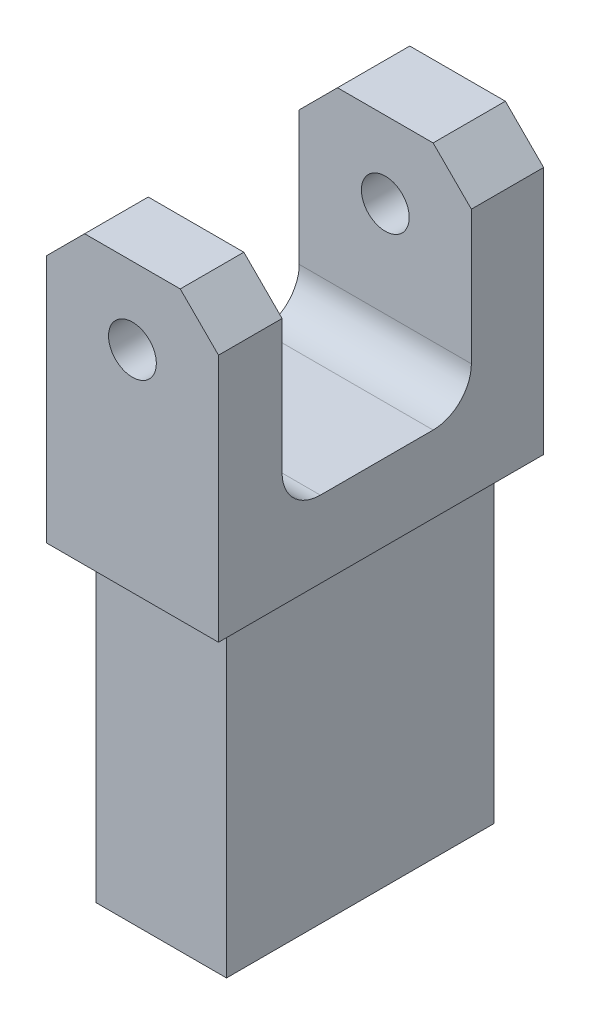
SolidWorks part; units mm, degrees
ref_plane "Спереди" through (0, 0, 0) normal (0, 0, 1) x (1, 0, 0)
ref_plane "Сверху" through (0, 0, 0) normal (0, 1, 0) x (1, 0, 0)
ref_plane "Справа" through (0, 0, 0) normal (1, 0, 0) x (0, 0, -1)
sketch "Эскиз1" plane through (0, 0, 0) normal (0, 1, 0) x (1, 0, 0)
  line L1 (1.598, -22.6241) -> (15.2463, -22.6241)
  line L2 (1.598, -22.6241) -> (1.598, -50.5962)
  line L3 (1.598, -50.5962) -> (15.2463, -50.5962)
  line L4 (15.2463, -22.6241) -> (15.2463, -50.5962)
extrude "Вытянуть1" add sketch "Эскиз1" along normal blind 33 from offset 18 offset against normal yes
sketch "Эскиз3" plane through (0, 15, 0) normal (0, 1, 0) x (1, 0, 0)
  line L0 (1.598, -36.6102) -> (-17.2651, -36.6102) construction
  line L2 (8.4222, -22.6241) -> (8.4222, -57.0135) construction
  line L4 (1.598, -50.5962) -> (15.2463, -50.5962) construction
  line L5 (15.2463, -50.5962) -> (15.2463, -22.6241) construction
  line L7 (17.4222, -53.6102) -> (-0.5778, -53.6102)
  line L8 (17.4222, -53.6102) -> (17.4222, -19.6102)
  line L9 (17.4222, -19.6102) -> (-0.5778, -19.6102)
  line L10 (-0.5778, -53.6102) -> (-0.5778, -19.6102)
  line L11 (17.4222, -53.6102) -> (-0.5778, -19.6102) construction
  line L12 (17.4222, -19.6102) -> (-0.5778, -53.6102) construction
  point P7 (8.4222, -36.6102)
extrude "Вытянуть2" add sketch "Эскиз3" along normal blind 30
sketch "Эскиз4" plane through (0, 45, 0) normal (0, 1, 0) x (1, 0, 0)
  line L5 (-1.3474, -46.9592) -> (19.6353, -46.9592)
  line L6 (-1.3474, -46.9592) -> (-1.3474, -27.1665)
  line L7 (-1.3474, -27.1665) -> (19.6353, -27.1665)
  line L8 (19.6353, -46.9592) -> (19.6353, -27.1665)
extrude "Вырез-Вытянуть1" cut sketch "Эскиз4" against normal blind 22
fillet "Скругление1" radius 4 2 edges at (8.4222, 23, 27.1665) (8.4222, 23, 46.9592)
sketch "Эскиз5" plane through (0, 0, 53.6102) normal (0, 0, 1) x (1, 0, 0)
  line L0 (8.4222, 43.1475) -> (8.4222, 26.7397) construction
  line L1 (-0.5778, 45) -> (17.4222, 45) construction
  circle A0 centre (8.4222, 37) radius 2.5
  dimension "D1" = 8
extrude "Вырез-Вытянуть2" cut sketch "Эскиз5" against normal through all
chamfer "Фаска1" distance 4 angle 45 4 edges at (17.4222, 45, 50.2847) (17.4222, 45, 23.3883) (-0.5778, 45, 50.2847) (-0.5778, 45, 23.3883)
